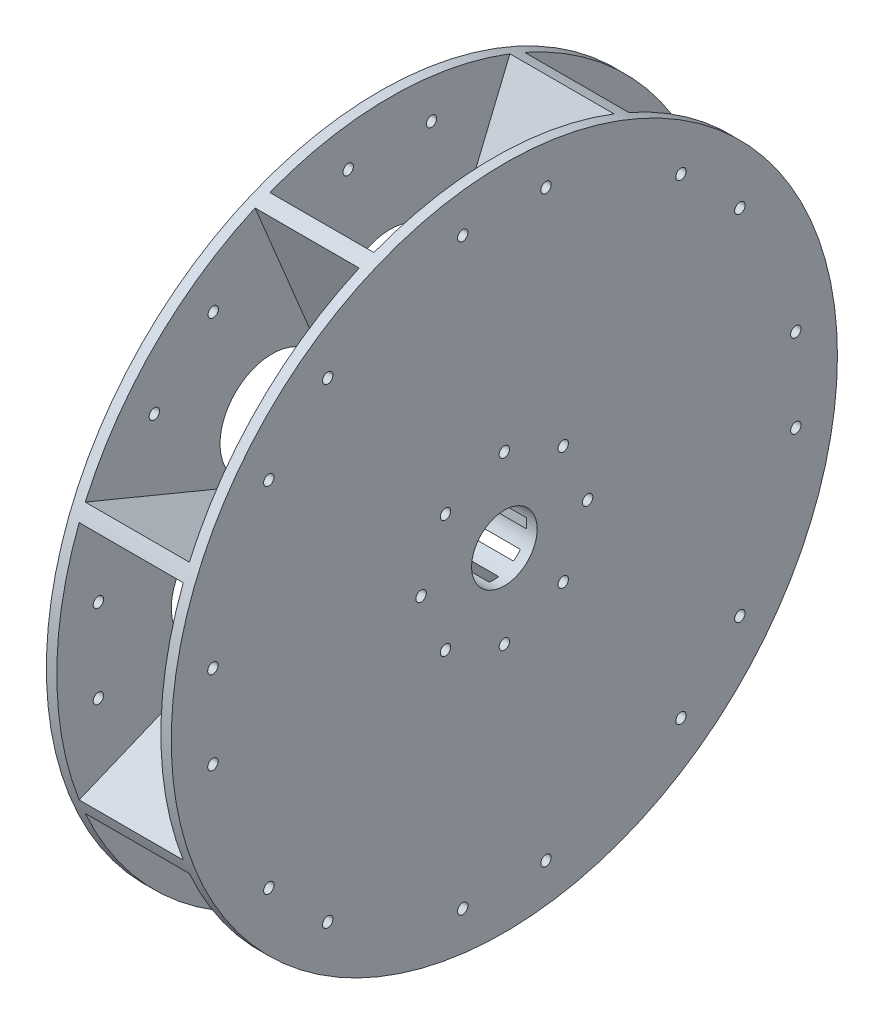
SolidWorks part; units mm, degrees
ref_plane "Front Plane" through (0, 0, 0) normal (0, 0, 1) x (1, 0, 0)
ref_plane "Top Plane" through (0, 0, 0) normal (0, 1, 0) x (1, 0, 0)
ref_plane "Right Plane" through (0, 0, 0) normal (1, 0, 0) x (0, 0, -1)
sketch "Sketch1" plane through (0, 0, 0) normal (1, 0, 0) x (0, 0, -1)
  circle A0 centre (0, 0) radius 203.2
  dimension "D1" = 406.4
extrude "Boss-Extrude1" add sketch "Sketch1" along normal blind 76.2
sketch "Sketch6" plane through (76.2, 0, 0) normal (1, 0, 0) x (0, 0, -1)
  line L0 (0, 0) -> (0, 177.8) construction
  circle A0 centre (0, 101.6) radius 31.75
  circle A1 centre (25.4, 177.8) radius 3.175
  circle A2 centre (-25.4, 177.8) radius 3.175
  circle A3 centre (0, 50.8) radius 3.175
  dimension "D1" = 63.5
  dimension "D2" = 6.35
  dimension "D6" = 6.35
  dimension "D3" = 101.6
  dimension "D4" = 76.2
  dimension "D5" = 25.4
  dimension "D7" = 50.8
extrude "Cut-Extrude1" cut sketch "Sketch6" against normal through all
pattern_circular "CirPattern1" count 8 every 45 about axis through (0, 0, 0) along (1, 0, 0) of "Cut-Extrude1"
ref_plane "Plane1" through (38.1, 0, 0) normal (1, 0, 0) x (0, 0, -1)
sketch "Sketch8" plane through (38.1, 0, 0) normal (1, 0, 0) x (0, 0, -1)
  line L0 (0, 0) -> (203.2, 0) construction
  line L1 (12.7, 0) -> (189.5385, -73.2489)
  line L10 (12.7, 0) -> (189.5385, 73.2489)
  circle A4 centre (0, 0) radius 203.2 construction
  arc A5 (189.5385, -73.2489) -> (189.5385, 73.2489) centre (0, 0) ccw
  dimension "D1" = 0
  dimension "D2" = 12.7
  dimension "D3" = 22.5
  dimension "D4" = 22.5
extrude "Cut-Extrude3" cut sketch "Sketch8" along normal mid plane 63.5
pattern_circular "CirPattern2" count 8 over 360 about axis through (0, 0, 0) along (1, 0, 0) of "Cut-Extrude3"
sketch "Sketch11" plane through (76.2, 0, 0) normal (1, 0, 0) x (0, 0, -1)
  circle A0 centre (0, 101.6) radius 31.75 construction
  circle A1 centre (0, 101.6) radius 31.75
extrude "Boss-Extrude2" add sketch "Sketch11" against normal blind 6.35
pattern_circular "CirPattern4" count 8 every 45 of "Boss-Extrude2"
sketch "Sketch12" plane through (0, 0, 0) normal (-1, 0, 0) x (0, 0, 1)
  line L0 (0, 0) -> (-35.921, 35.921) construction
  line L1 (0, 0) -> (35.921, -35.921) construction
  line L2 (0, 0) -> (-35.921, -35.921) construction
  line L3 (0, 0) -> (35.921, 35.921) construction
  circle A0 centre (0, 0) radius 20
  dimension "D1" = 40
extrude "Cut-Extrude4" cut sketch "Sketch12" against normal up to surface (76.2 mm away) up to face at (76.2, -105.518, 145.9292)
